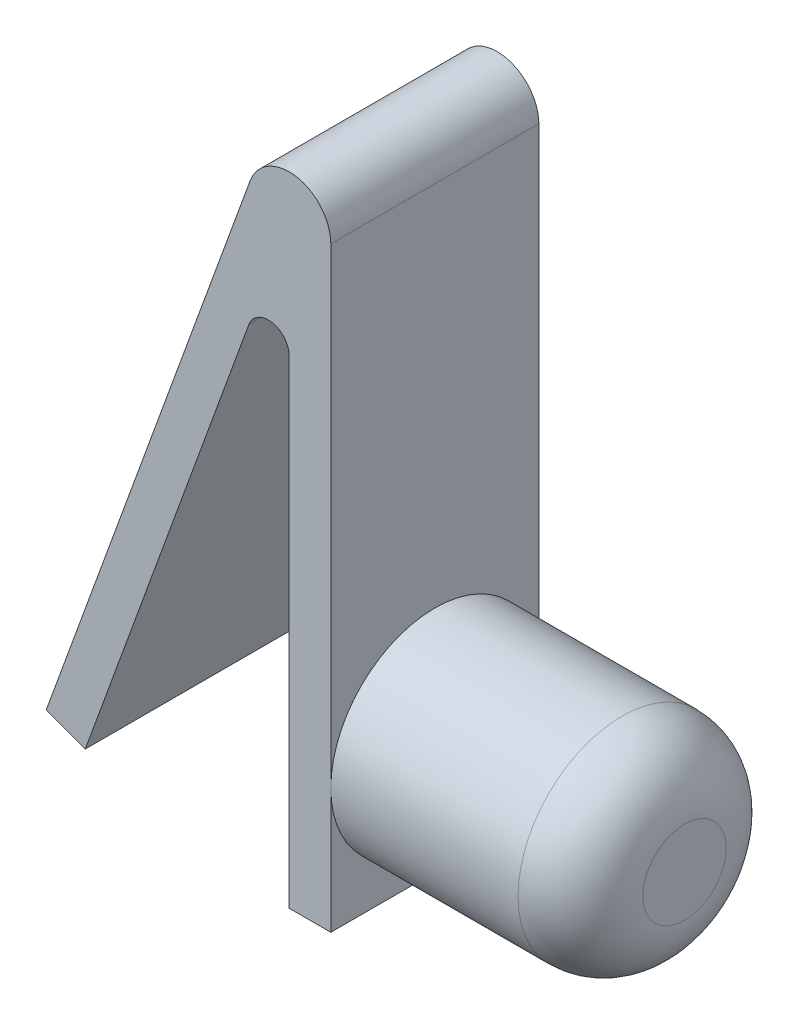
SolidWorks part; units mm, degrees
ref_plane "Front Plane" through (0, 0, 0) normal (0, 0, 1) x (1, 0, 0)
ref_plane "Top Plane" through (0, 0, 0) normal (0, 1, 0) x (1, 0, 0)
ref_plane "Right Plane" through (0, 0, 0) normal (1, 0, 0) x (0, 0, -1)
sketch "Sketch1" plane through (0, 0, 0) normal (0, 0, 1) x (1, 0, 0)
  line L0 (0, 0) -> (0, 11.4931)
  line L1 (-0.9698, 11.6641) -> (-4.9007, 0.8641)
  line L2 (-4.9007, 0.8641) -> (-5.8404, 1.2061)
  line L3 (-5.8404, 1.2061) -> (-0.9397, 14.6707)
  line L4 (1, 14.3287) -> (1, 0)
  line L5 (1, 0) -> (0, 0)
  arc A0 (0, 11.4931) -> (-0.9698, 11.6641) centre (-0.5, 11.4931) ccw
  arc A1 (-0.9397, 14.6707) -> (1, 14.3287) centre (0, 14.3287) cw
  point P12 (1, 20)
  dimension "D6" = 0.5
  dimension "D7" = 1
  dimension "D1" = 1
  dimension "D2" = 1
  dimension "D3" = 20
  dimension "D4" = 20
  dimension "D5" = 20
extrude "Boss-Extrude1" add sketch "Sketch1" along normal blind 5 contours L4 L5 L0 A0 L1 L2 L3 A1
sketch "Sketch2" plane through (1, 0, 0) normal (1, 0, 0) x (0, 0, -1)
  line L0 (-2.5, 0.6938) -> (-2.5, 11.8267) construction
  line L1 (-5, 0) -> (0, 0)
  circle A0 centre (-2.5, 3) radius 2.5
  point P6 (-2.5, 0)
  point P9 (0, 0)
  dimension "D2" = 5
  dimension "D1" = 3
extrude "Boss-Extrude2" add sketch "Sketch2" along normal blind 6 contours L0 A0 | A0 L0
fillet "Fillet1" radius 1.5 1 edges at (7, 5.5, 2.5)
